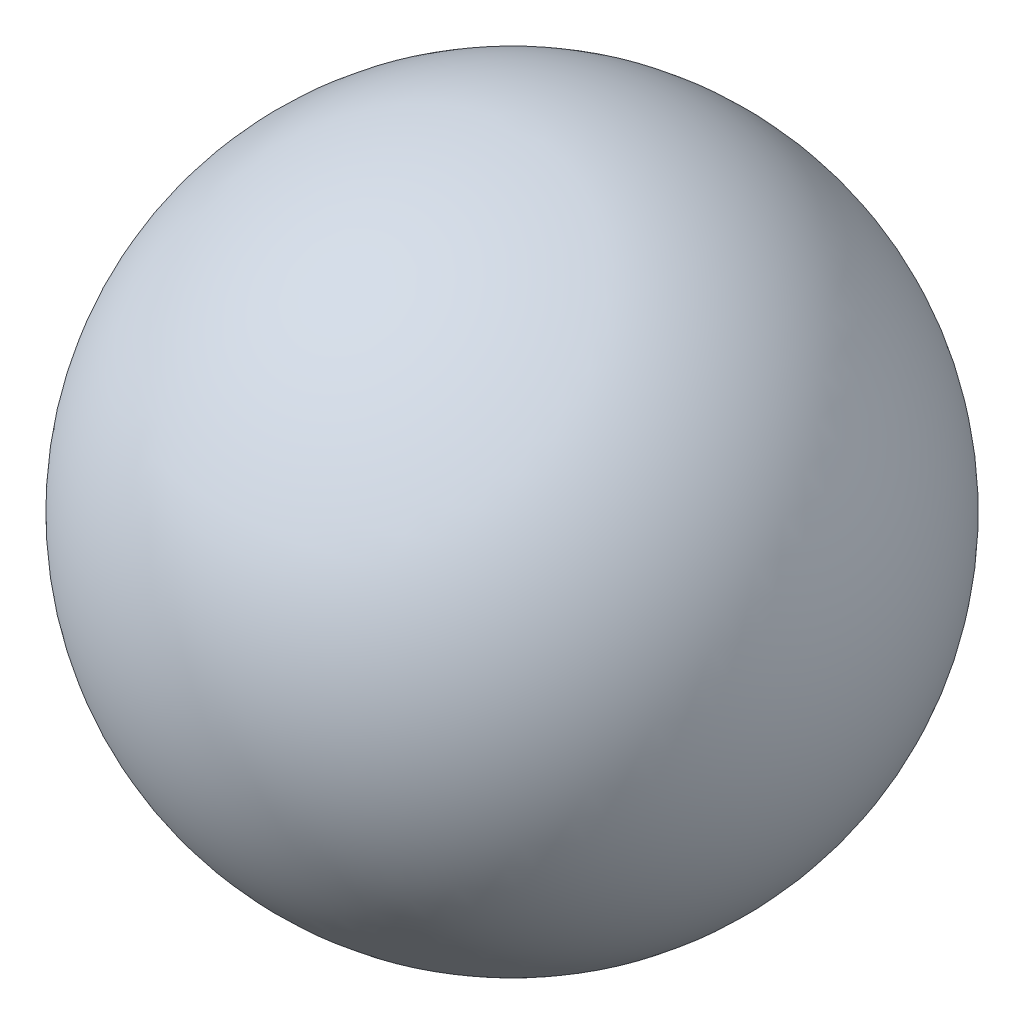
SolidWorks part; units mm, degrees
material "Chrome Stainless Steel"
ref_plane "Front Plane" through (0, 0, 0) normal (0, 0, 1) x (1, 0, 0)
ref_plane "Top Plane" through (0, 0, 0) normal (0, 1, 0) x (1, 0, 0)
ref_plane "Right Plane" through (0, 0, 0) normal (1, 0, 0) x (0, 0, -1)
sketch "Sketch1" plane through (0, 0, 0) normal (0, 0, 1) x (1, 0, 0)
  line L0 (0, 1.389) -> (0, -1.389) construction
  line L1 (0, -1.389) -> (0, 1.389)
  arc A0 (0, -1.389) -> (0, 1.389) centre (0, 0) ccw
  point P4 (0, 0)
revolve "Revolve1" add sketch "Sketch1" angle 360 about L0
